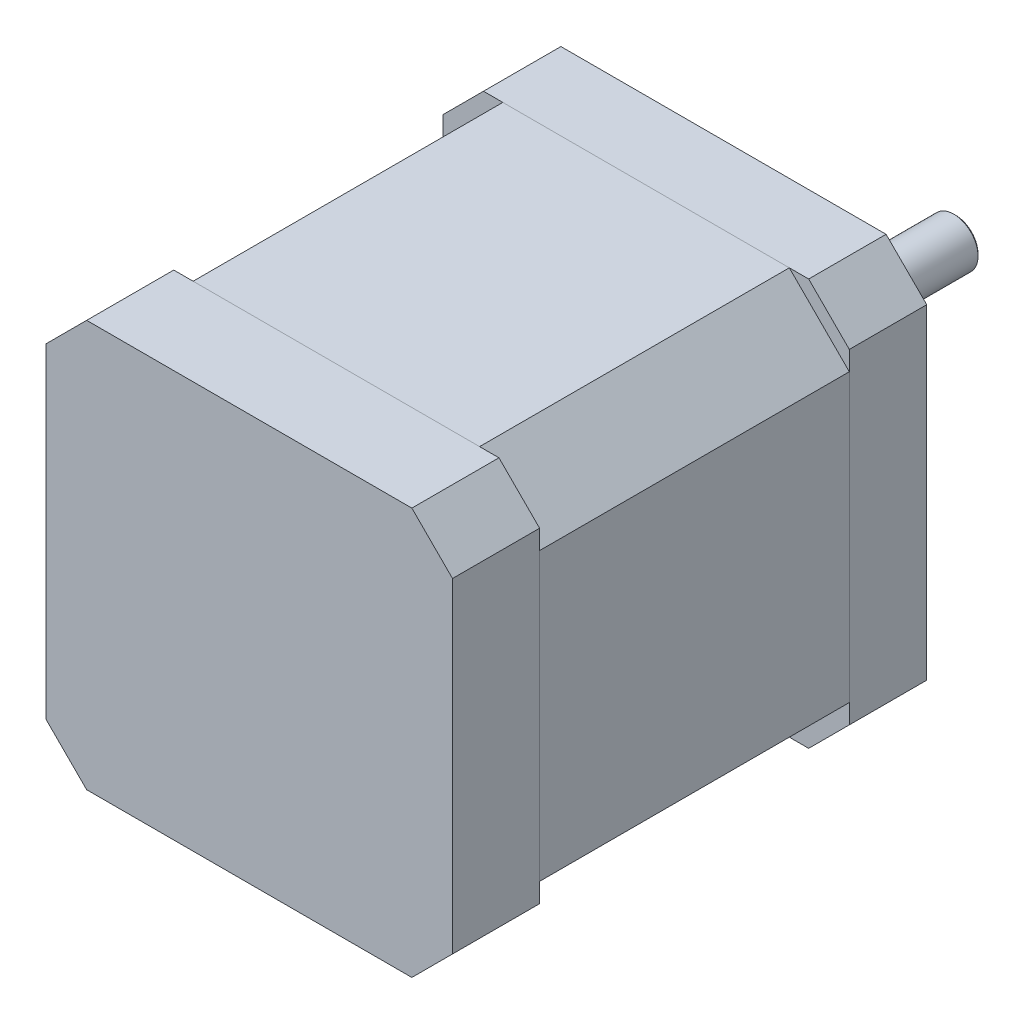
SolidWorks part; units mm, degrees
ref_plane "Plan de face" through (0, 0, 0) normal (0, 0, 1) x (1, 0, 0)
ref_plane "Plan de dessus" through (0, 0, 0) normal (0, 1, 0) x (1, 0, 0)
ref_plane "Plan de droite" through (0, 0, 0) normal (1, 0, 0) x (0, 0, -1)
sketch "Esquisse1" plane through (0, 0, 0) normal (0, 0, 1) x (1, 0, 0)
  line L1 (-21, 21) -> (21, 21)
  line L2 (-21, 21) -> (-21, -21)
  line L3 (-21, -21) -> (21, -21)
  line L4 (21, 21) -> (21, -21)
  line L5 (-21, 21) -> (21, -21) construction
  line L6 (-21, -21) -> (21, 21) construction
  point P0 (0, 0)
  dimension "D1" = 42
  dimension "D2" = 42
extrude "Boss.-Extru.1" add sketch "Esquisse1" along normal blind 8
chamfer "Chanfrein1" distance 4.2 angle 45 4 edges at (-21, -21, 4) (-21, 21, 4) (21, 21, 4) (21, -21, 4)
sketch "Esquisse3" plane through (0, 0, 8) normal (0, 0, 1) x (1, 0, 0)
  line L0 (-21, 14.8) -> (-14.8, 21)
  line L1 (-14.8, 21) -> (14.8, 21)
  line L2 (-21, 14.8) -> (-21, -14.8)
  line L3 (-14.8, -21) -> (14.8, -21)
  line L4 (21, 14.8) -> (21, -14.8)
  line L5 (-21, 21) -> (21, -21) construction
  line L6 (-21, -21) -> (21, 21) construction
  line L7 (14.8, 21) -> (21, 14.8)
  line L8 (14.8, -21) -> (21, -14.8)
  line L9 (-21, -14.8) -> (-14.8, -21)
  point P0 (0, 0)
  dimension "D1" = 42
  dimension "D2" = 42
extrude "Boss.-Extru.2" add sketch "Esquisse3" along normal blind 32 separate body
sketch "Esquisse4" plane through (0, 0, 40) normal (0, 0, 1) x (1, 0, 0)
  line L1 (-21, -21) -> (21, -21)
  line L2 (-21, -21) -> (-21, 21)
  line L3 (-21, 21) -> (21, 21)
  line L4 (21, -21) -> (21, 21)
  line L5 (-21, -21) -> (21, 21) construction
  line L6 (-21, 21) -> (21, -21) construction
  point P0 (0, 0)
  dimension "D1" = 42
  dimension "D2" = 42
extrude "Boss.-Extru.3" add sketch "Esquisse4" along normal blind 9 separate body
chamfer "Chanfrein3" distance 4.2 angle 45 4 edges at (21, 21, 44.5) (21, -21, 44.5) (-21, -21, 44.5) (-21, 21, 44.5)
sketch "Esquisse5" plane through (0, 0, 0) normal (0, 0, -1) x (-1, 0, 0)
  circle A0 centre (0, 0) radius 11
  dimension "D1" = 22
extrude "Boss.-Extru.4" add sketch "Esquisse5" along normal blind 2
sketch "Esquisse6" plane through (0, 0, -2) normal (0, 0, -1) x (-1, 0, 0)
  circle A0 centre (0, 0) radius 4.5
  dimension "D1" = 9
extrude "Enlèv. mat.-Extru.1" cut sketch "Esquisse6" against normal blind 3
sketch "Esquisse7" plane through (0, 0, 1) normal (0, 0, -1) x (-1, 0, 0)
  circle A0 centre (0, 0) radius 2.5
  dimension "D1" = 5
extrude "Boss.-Extru.5" add sketch "Esquisse7" along normal blind 25
chamfer "Chanfrein4" distance 0.2 angle 45 1 edges at (-2.5, 0, -24)
sketch "Esquisse8" plane through (0, 0, 0) normal (0, 0, -1) x (-1, 0, 0)
  line L1 (-15.5, 15.5) -> (15.5, 15.5) construction
  line L2 (-15.5, 15.5) -> (-15.5, -15.5) construction
  line L3 (-15.5, -15.5) -> (15.5, -15.5) construction
  line L4 (15.5, 15.5) -> (15.5, -15.5) construction
  line L5 (-15.5, 15.5) -> (15.5, -15.5) construction
  line L6 (-15.5, -15.5) -> (15.5, 15.5) construction
  circle A0 centre (-15.5, 15.5) radius 1.5
  circle A1 centre (15.5, 15.5) radius 1.5
  circle A2 centre (15.5, -15.5) radius 1.5
  circle A3 centre (-15.5, -15.5) radius 1.5
  point P0 (0, 0)
  dimension "D3" = 3
  dimension "D1" = 31
  dimension "D2" = 31
extrude "Enlèv. mat.-Extru.2" cut sketch "Esquisse8" against normal blind 5
chamfer "Chanfrein5" distance 0.2 angle 45 4 edges at (14, -15.5, 0) (-17, -15.5, 0) (-17, 15.5, 0) (14, 15.5, 0)
sketch "Esquisse9" plane through (-21, 0, 0) normal (-1, 0, 0) x (0, 0, 1)
  line L0 (43.5, 0) -> (40, 0) construction
  line L1 (40, -4) -> (47, -4)
  line L2 (40, -4) -> (40, 4)
  line L3 (40, 4) -> (47, 4)
  line L4 (47, -4) -> (47, 4)
  line L5 (40, -4) -> (47, 4) construction
  line L6 (40, 4) -> (47, -4) construction
  line L7 (40, 16.8) -> (40, -16.8) construction
  point P0 (43.5, 0)
  dimension "D1" = 7
  dimension "D2" = 8
extrude "Enlèv. mat.-Extru.3" cut sketch "Esquisse9" against normal blind 2
